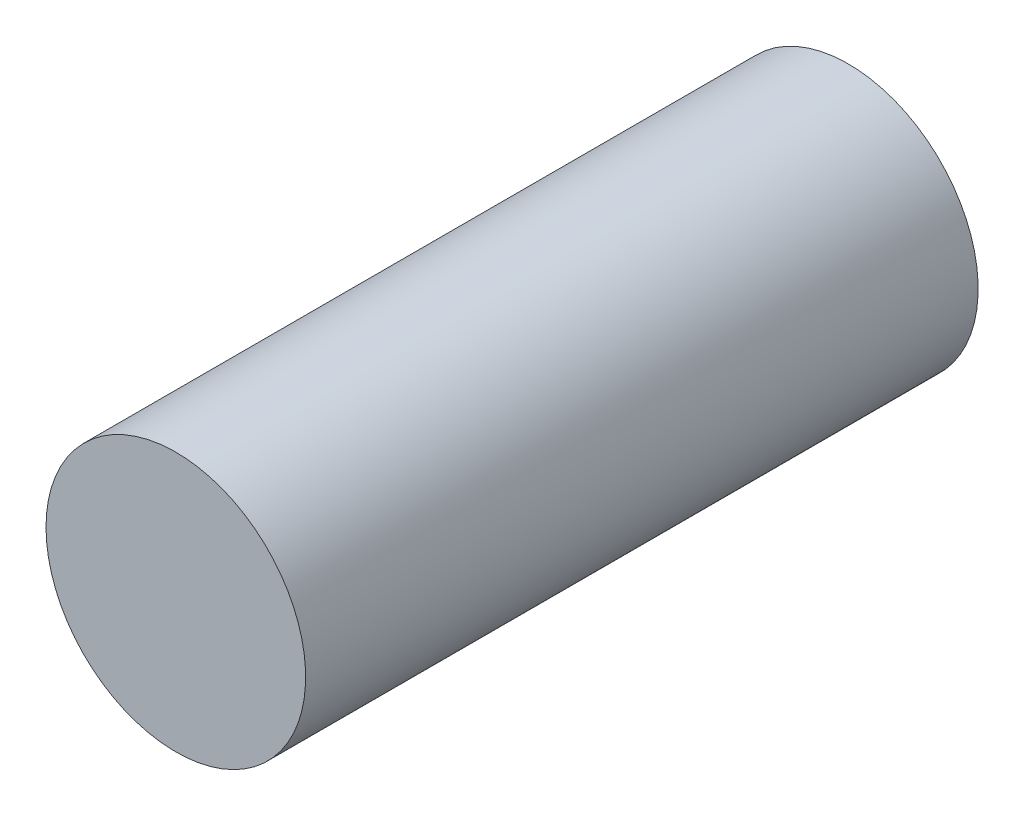
SolidWorks part; units mm, degrees
material "6061-T6 (SS)"
ref_plane "Front Plane" through (0, 0, 0) normal (0, 0, 1) x (1, 0, 0)
ref_plane "Top Plane" through (0, 0, 0) normal (0, 1, 0) x (1, 0, 0)
ref_plane "Right Plane" through (0, 0, 0) normal (1, 0, 0) x (0, 0, -1)
sketch "Sketch1" plane through (0, 0, 0) normal (0, 0, 1) x (1, 0, 0)
  circle A0 centre (0, 0) radius 10
  dimension "D1" = 20
extrude "Boss-Extrude1" add sketch "Sketch1" along normal blind 51.8
